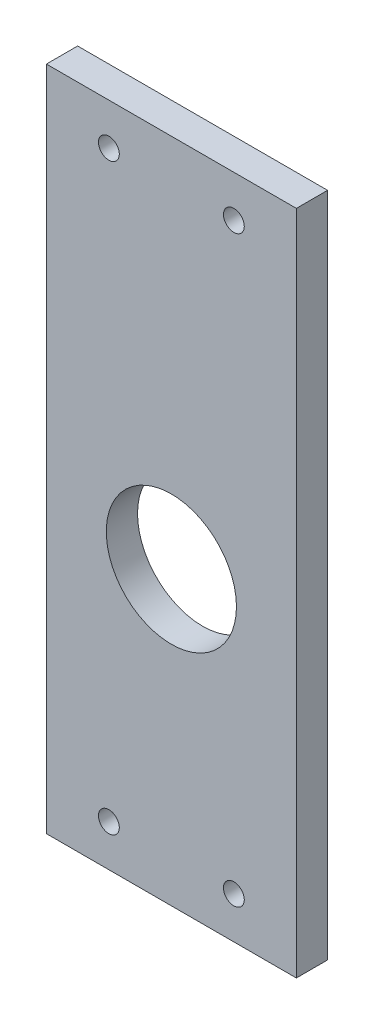
SolidWorks part; units mm, degrees
ref_plane "Front Plane" through (0, 0, 0) normal (0, 0, 1) x (1, 0, 0)
ref_plane "Top Plane" through (0, 0, 0) normal (0, 1, 0) x (1, 0, 0)
ref_plane "Right Plane" through (0, 0, 0) normal (1, 0, 0) x (0, 0, -1)
sketch "Sketch1" plane through (0, 0, 0) normal (0, 0, 1) x (1, 0, 0)
  line L1 (0, 0) -> (76.2, 0)
  line L2 (0, 0) -> (0, 203.2)
  line L3 (0, 203.2) -> (76.2, 203.2)
  line L4 (76.2, 0) -> (76.2, 203.2)
  dimension "D1" = 203.2
  dimension "D2" = 76.2
extrude "Boss-Extrude1" add sketch "Sketch1" along normal blind 9.525
sketch "Sketch2" plane through (0, 0, 9.525) normal (0, 0, 1) x (1, 0, 0)
  line L2 (0, 0) -> (76.2, 0) construction
  line L3 (76.2, 0) -> (76.2, 203.2) construction
  circle A0 centre (38.1, 88.9) radius 19.8438
  dimension "D1" = 39.6875
  dimension "D2" = 88.9
  dimension "D3" = 38.1
extrude "Cut-Extrude1" cut sketch "Sketch2" against normal up to surface (9.525 mm away) up to face at (38.1, 101.6, 0)
sketch "Sketch3" plane through (0, 0, 9.525) normal (0, 0, 1) x (1, 0, 0)
  line L0 (76.2, 203.2) -> (0, 203.2) construction
  line L1 (0, 0) -> (76.2, 0) construction
  line L2 (0, 203.2) -> (0, 0) construction
  line L3 (76.2, 0) -> (76.2, 203.2) construction
  circle A0 centre (19.05, 190.5) radius 3.175
  circle A1 centre (57.15, 190.5) radius 3.175
  circle A2 centre (19.05, 12.7) radius 3.175
  circle A3 centre (57.15, 12.7) radius 3.175
  dimension "D1" = 6.35
  dimension "D2" = 12.7
  dimension "D3" = 12.7
  dimension "D4" = 19.05
  dimension "D5" = 19.05
extrude "Cut-Extrude2" cut sketch "Sketch3" against normal up to surface (9.525 mm away) up to face at (18.2563, 88.9, 0)
